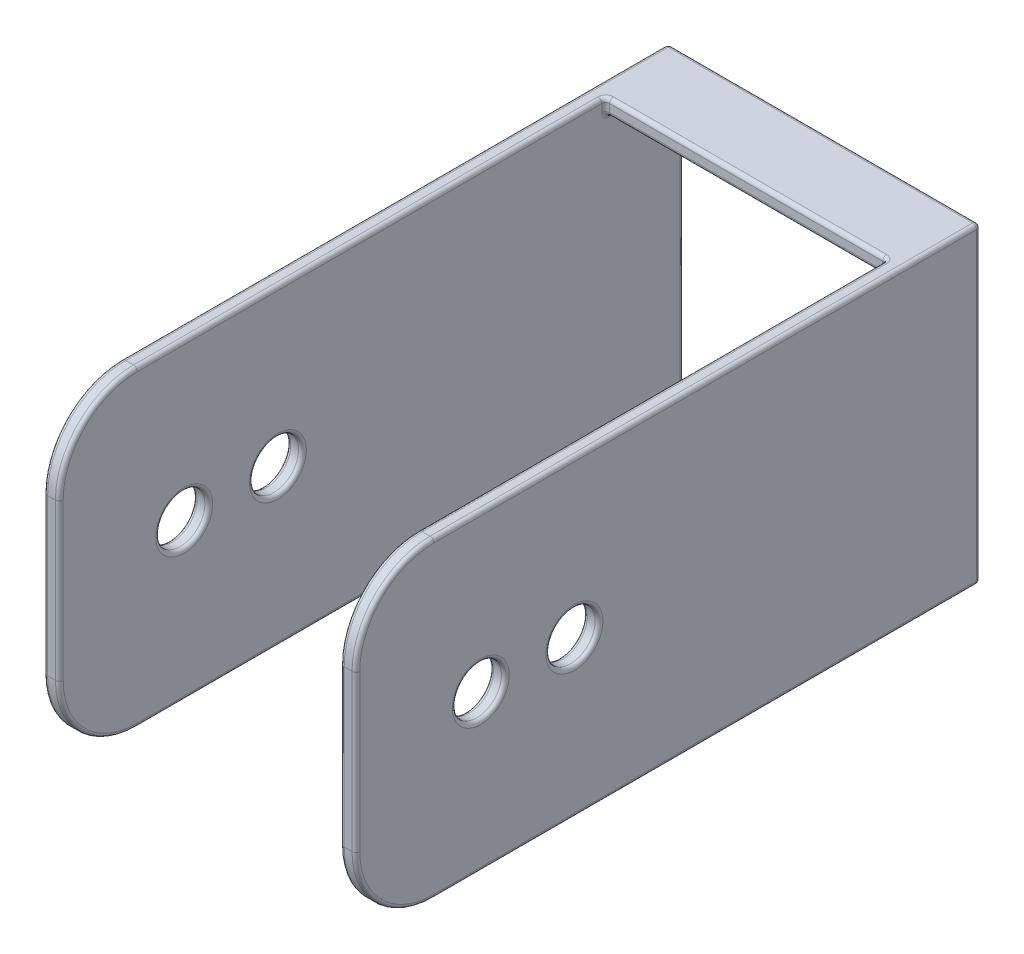
SolidWorks part; units mm, degrees
material "6061 Legierung"
ref_plane "Ebene vorne" through (0, 0, 0) normal (0, 0, 1) x (1, 0, 0)
ref_plane "Ebene oben" through (0, 0, 0) normal (0, 1, 0) x (1, 0, 0)
ref_plane "Ebene rechts" through (0, 0, 0) normal (1, 0, 0) x (0, 0, -1)
sketch "Skizze1" plane through (0, 0, 0) normal (0, 0, 1) x (1, 0, 0)
  line L1 (-20, -20) -> (20, -20)
  line L2 (-20, -20) -> (-20, 20)
  line L3 (-20, 20) -> (20, 20)
  line L4 (20, -20) -> (20, 20)
  line L5 (-20, -20) -> (20, 20) construction
  line L6 (-20, 20) -> (20, -20) construction
  line L7 (-18, -18) -> (18, -18)
  line L8 (-18, -18) -> (-18, 18)
  line L9 (-18, 18) -> (18, 18)
  line L10 (18, -18) -> (18, 18)
  line L11 (-18, -18) -> (18, 18) construction
  line L12 (-18, 18) -> (18, -18) construction
  point P0 (0, 0)
  point P6 (0, 0)
  dimension "D1" = 40
  dimension "D2" = 40
  dimension "D3" = 2
  dimension "D4" = 2
extrude "Aufsatz-Linear austragen1" add sketch "Skizze1" along normal blind 80
sketch "Skizze2" plane through (0, 20, 0) normal (0, 1, 0) x (1, 0, 0)
  line L0 (20, -80) -> (20, 0) construction
  line L1 (-18, -80) -> (18, -80)
  line L2 (-18, -80) -> (-18, -10)
  line L3 (-18, -10) -> (18, -10)
  line L4 (18, -80) -> (18, -10)
  line L5 (20, 0) -> (-20, 0) construction
  dimension "D1" = 2
  dimension "D2" = 10
extrude "Schnitt-Linear austragen1" cut sketch "Skizze2" against normal through all
sketch "Skizze3" plane through (20, 0, 0) normal (1, 0, 0) x (0, 0, -1)
  line L0 (-80, -20) -> (-80, 20) construction
  circle A0 centre (-64, 0) radius 3.15
  circle A1 centre (-52, 0) radius 3.15
  dimension "D1" = 6.3
  dimension "D3" = 6.3
  dimension "D2" = 16
  dimension "D4" = 12
extrude "Schnitt-Linear austragen2" cut sketch "Skizze3" against normal through all
fillet "Verrundung1" radius 10 4 edges at (-19, -20, 80) (19, -20, 80) (19, 20, 80) (-19, 20, 80)
fillet "Verrundung2" radius 0.5 48 edges at (0, -18, 0) (0, -18, 10) (0, 18, 0) (0, 18, 10) (-18, 17.0711, 77.0711) (-18, 19, 10) (-18, 18, 5) (-18, 0, 0) (-18, -18, 5) (-18, -19, 10) (-18, -17.0711, 77.0711) (-18, 0, 80) (-18, 0, 60.85) (18, -19, 10) (18, -18, 5) (18, 0, 0) (18, 18, 5) (18, 19, 10) (18, 17.0711, 77.0711) (18, 0, 80) (18, -17.0711, 77.0711) (18, 0, 67.15) (0, -20, 10) (18, -20, 40) (0, -20, 0) (-18, -20, 40) (0, 20, 10) (-18, 20, 40) (0, 20, 0) (18, 20, 40) (-20, 0, 0) (-20, 20, 35) (-20, 17.0711, 77.0711) (-20, 0, 80) (-20, -17.0711, 77.0711) (-20, -20, 35) (-20, 0, 60.85) (20, 17.0711, 77.0711) (20, 20, 35) (20, 0, 0) (20, -20, 35) (20, -17.0711, 77.0711) (20, 0, 80) (20, 0, 60.85) (-18, 0, 48.85) (18, 0, 55.15) (-20, 0, 48.85) (20, 0, 48.85)
